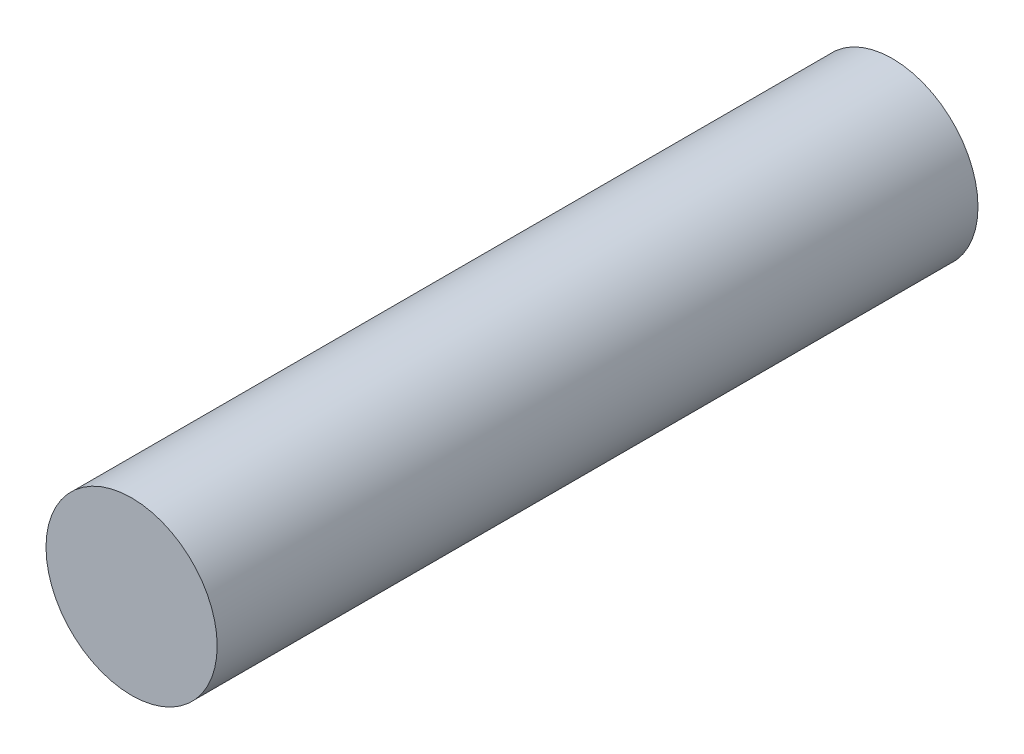
SolidWorks part; units mm, degrees
ref_plane "前基準面" through (0, 0, 0) normal (0, 0, 1) x (1, 0, 0)
ref_plane "上基準面" through (0, 0, 0) normal (0, 1, 0) x (1, 0, 0)
ref_plane "右基準面" through (0, 0, 0) normal (1, 0, 0) x (0, 0, -1)
sketch "草圖1" plane through (0, 0, 0) normal (0, 0, 1) x (1, 0, 0)
  circle A0 centre (0, 0) radius 2.25
  dimension "D1" = 4.5
extrude "填料-伸長1" add sketch "草圖1" along normal blind 20
